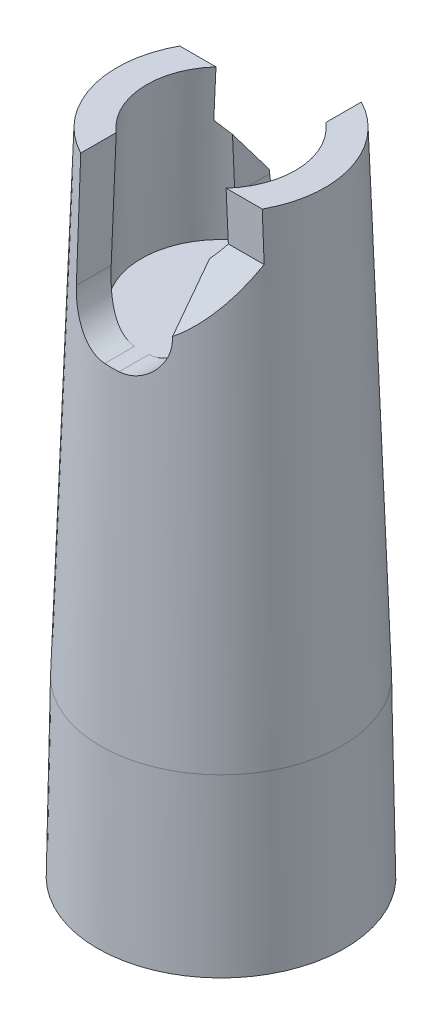
SolidWorks part; units mm, degrees
ref_plane "Front Plane" through (0, 0, 0) normal (0, 0, 1) x (1, 0, 0)
ref_plane "Top Plane" through (0, 0, 0) normal (0, 1, 0) x (1, 0, 0)
ref_plane "Right Plane" through (0, 0, 0) normal (1, 0, 0) x (0, 0, -1)
sketch "Sketch1" plane through (0, 0, 0) normal (0, 1, 0) x (1, 0, 0)
  circle A0 centre (0, 0) radius 2.9972
  dimension "D1" = 5.9944
extrude "insert" add sketch "Sketch1" along normal blind 11.811 draft 2 and the other way blind 4.318 draft 1
ref_plane "top of valve" through (0, 0, 0) normal (0, -1, 0) x (-1, 0, 0)
sketch "Sketch2" plane through (0, 0, 0) normal (0, -1, 0) x (1, 0, 0)
  circle A0 centre (0, 0) radius 2.2606
  dimension "D1" = 4.5212
extrude "insert bore" cut sketch "Sketch2" against normal through all draft 2 and the other way through all
sketch "Sketch3" plane through (0, 0, 0) normal (0, 0, 1) x (1, 0, 0)
  line L0 (0, 0) -> (0, 11.811) construction
  line L1 (1.8482, 11.811) -> (-1.8482, 11.811) construction
  line L2 (2.5848, 11.811) -> (-2.5848, 11.811) construction
  line L3 (-1.1938, 11.811) -> (1.1938, 11.811)
  line L4 (-1.1938, 11.811) -> (-1.1938, 9.017)
  line L5 (-0.1778, 8.001) -> (0.1778, 8.001)
  line L6 (1.1938, 11.811) -> (1.1938, 9.017)
  arc A0 (-0.1778, 8.001) -> (-1.1938, 9.017) centre (-0.1778, 9.017) cw
  arc A1 (1.1938, 9.017) -> (0.1778, 8.001) centre (0.1778, 9.017) cw
  dimension "D3" = 1.016
  dimension "D1" = 3.81
  dimension "D2" = 2.3876
extrude "pass cut" cut sketch "Sketch3" against normal through all and the other way through all
sketch "Sketch4" plane through (0, 0, 0) normal (1, 0, 0) x (0, 0, -1)
  line L0 (1.2424, 11.811) -> (2.7072, 11.811)
  line L1 (2.2925, 11.811) -> (-2.2925, 11.811) construction
  line L2 (2.7072, 11.811) -> (2.7072, 8.7031)
  line L3 (2.7072, 8.7031) -> (1.2424, 10.6387)
  line L4 (1.2424, 10.6387) -> (1.2424, 11.811)
extrude "pass chip" cut sketch "Sketch4" against normal through all
pattern_circular "CirPattern1" count 2 over 360 about axis through (0, -4.318, 0) along (0, 1, 0) of "pass chip"
ref_plane "Plane1" through (0, 8.001, 0) normal (0, -1, 0) x (-1, 0, 0)
sketch "Sketch5" plane through (0, 8.001, 0) normal (0, -1, 0) x (-1, 0, 0)
  circle A0 centre (0, 0) radius 2.032
  dimension "D1" = 4.064
extrude "Boss-Extrude1" add sketch "Sketch5" along normal blind 1.0922
